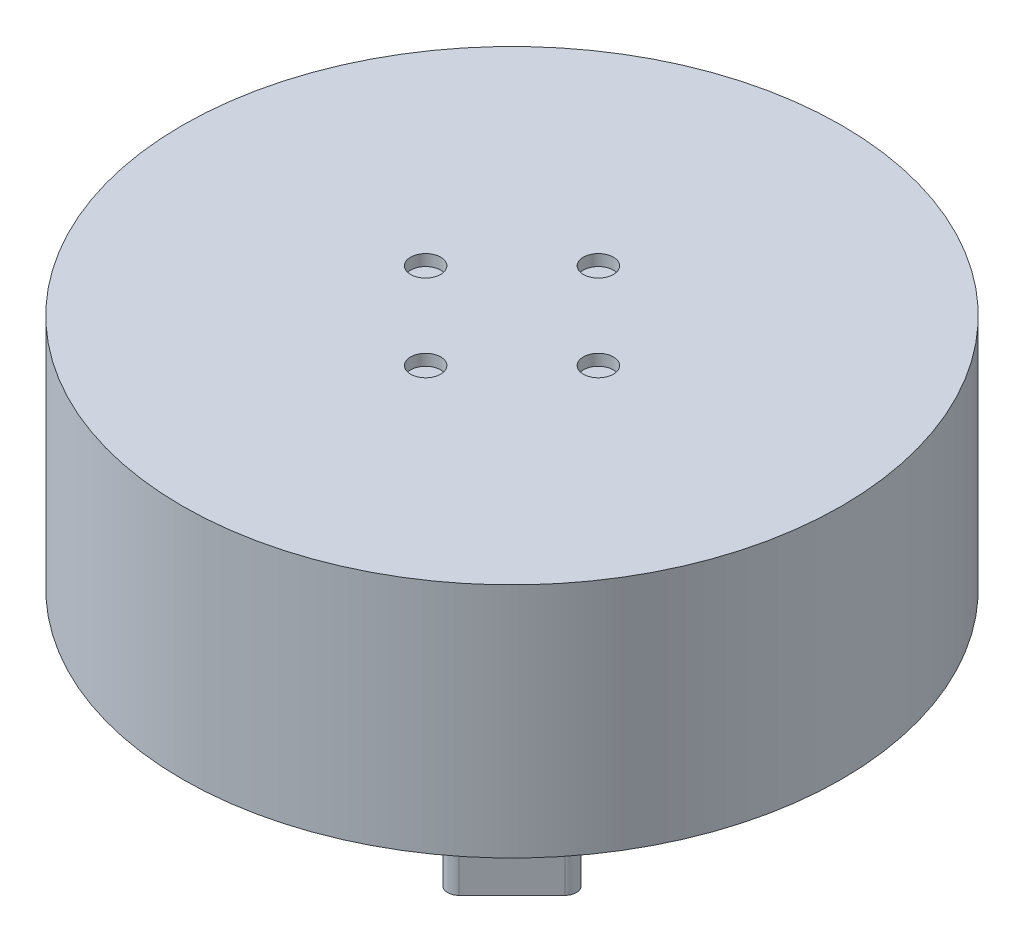
SolidWorks part; units mm, degrees
ref_plane "Front Plane" through (0, 0, 0) normal (0, 0, 1) x (1, 0, 0)
ref_plane "Top Plane" through (0, 0, 0) normal (0, 1, 0) x (1, 0, 0)
ref_plane "Right Plane" through (0, 0, 0) normal (1, 0, 0) x (0, 0, -1)
sketch "Sketch1" plane through (0, 0, 0) normal (0, 1, 0) x (1, 0, 0)
  circle A0 centre (0, 0) radius 43.9
  dimension "D1" = 87.8
extrude "Boss-Extrude1" add sketch "Sketch1" along normal blind 31.5
sketch "Sketch2" plane through (0, 0, 0) normal (0, -1, 0) x (1, 0, 0)
  circle A0 centre (0, 0) radius 18 construction
  circle A1 centre (0, 18) radius 2
  circle A2 centre (18, 0) radius 2
  circle A3 centre (0, -18) radius 2
  circle A4 centre (-18, 0) radius 2
  point P14 (0, 0)
  dimension "D1" = 36
  dimension "D2" = 4
  dimension "D3" = 4
extrude "Cut-Extrude1" cut sketch "Sketch2" against normal blind 1.5
sketch "Sketch3" plane through (0, 0, 0) normal (0, -1, 0) x (1, 0, 0)
  line L0 (0, 0) -> (0, 18) construction
  line L1 (0, 18) -> (18, 0) construction
  line L2 (18, 0) -> (0, 0) construction
  line L3 (0, 0) -> (28.2843, 28.2843) construction
  line L4 (24.7487, 31.8198) -> (31.8198, 24.7487) construction
  line L5 (26.5165, 33.5876) -> (33.5876, 26.5165) construction
  line L6 (22.981, 30.052) -> (30.052, 22.981) construction
  line L7 (25.8094, 32.8805) -> (32.8805, 25.8094)
  line L8 (23.6881, 30.7591) -> (30.7591, 23.6881)
  arc A0 (26.5165, 33.5876) -> (22.981, 30.052) centre (24.7487, 31.8198) ccw construction
  arc A1 (30.052, 22.981) -> (33.5876, 26.5165) centre (31.8198, 24.7487) ccw construction
  arc A2 (30.7591, 23.6881) -> (32.8805, 25.8094) centre (31.8198, 24.7487) ccw
  arc A3 (25.8094, 32.8805) -> (23.6881, 30.7591) centre (24.7487, 31.8198) ccw
  point P9 (28.2843, 28.2843)
  dimension "D3" = 2.5
  dimension "D1" = 40
  dimension "D2" = 10
  dimension "D4" = 1
extrude "Boss-Extrude2" add sketch "Sketch3" along normal blind 6
sketch "Sketch4" plane through (0, 31.5, 0) normal (0, 1, 0) x (1, 0, 0)
  circle A0 centre (0, 0) radius 11.5 construction
  circle A1 centre (0, 11.5) radius 2
  circle A2 centre (11.5, 0) radius 2
  circle A3 centre (0, -11.5) radius 2
  circle A4 centre (-11.5, 0) radius 2
  point P14 (0, 0)
  dimension "D2" = 4
  dimension "D3" = 4
  dimension "D1" = 23
extrude "Cut-Extrude2" cut sketch "Sketch4" against normal blind 1.5
equation "\"Np\"= 65"
equation "\"module\"= 0.5"
equation "\"pressure angle\"= 20.0deg"
equation "\"h_a\"= 0.5"
equation "\"h_b\"= 0.625"
equation "\"clr_tip_root\"= 0.125"
equation "\"dp_p\"= 32.5"
equation "\"db_p\"= 30.540010175542022"
equation "\"fw_p\"= 22.13479809822934"
equation "\"alpha_p\"= 0.8539582918412485"
equation "\"beta_p\"= 1.0613141855482722"
equation "\"Nr\"= 155"
equation "\"pressure_angle\"= 20.0deg"
equation "\"h_f\"= 0.625"
equation "\"dp_r\"= 77.5"
equation "\"db_r\"= 72.8261781109079"
equation "\"fw_r\"= 22.13479809822934"
equation "\"alpha_r\"= 0.8539582918412449"
equation "\"beta_r\"= 2.869206906263135"
equation "\"bearing_ID\"= 55"
equation "\"bearing_OD\"= 72"
equation "\"bearing_height\"= 9"
equation "\"clearance_planet\"= 1.5"
equation "\"case_dist\"= 6.5"
equation "\"Motor_case_OD_max\"= 112.3"
equation "\"case_mounting_PCD\"= 104.8"
equation "\"bearing mount thickness\"= 8"
equation "\"case_mounting_hole_dia\"= 3"
equation "\"output_mounting_PCD\"= 80"
equation "\"output_mounting_hole_dia\"= 4"
equation "\"clearance_case_mount_holes_shell_thickness\"= 1"
equation "\"motor_case_OD_base\"= 102.8"
equation "\"sec_carrier_thickness\"= 5"
equation "\"sun_coupler_hub_thickness\"= 4"
equation "\"clearance_sun_coupler_sec_carrier\"= 1.5"
equation "\"clearance_motor_and_case\"= 5"
equation "\"motor_OD\"= 87.8"
equation "\"Motor_case_thickness\"= 2.5"
equation "\"Motor_case_ID\"= 97.8"
equation "\"case_mounting_hole_shift\"= 1.0"
equation "\"output_mounting_nut_wrench_size\"= 7"
equation "\"output_mounting_nut_thickness\"= 3.2"
equation "\"case_mounting_hole_allen_socket_dia\"= 5.5"
equation "\"output_mounting_nut_depth\"= 3"
equation "\"case_mounting_bolt_depth\"= 4.5"
equation "\"Ns\"= 25"
equation "\"ring_radial_thickness\"= 5.0"
equation "\"ring_OD\"= 87.5"
equation "\"ring_to_chamfer_clearance\"= 2"
equation "\"Motor_case_OD_base_to_chamfer\"= 5"
equation "\"pattern_offset_from_motor_case_OD_base\"= 3"
equation "\"pattern_bulge_dia\"= 3"
equation "\"pattern_num_bulge\"= 18"
equation "\"pattern_depth\"= 2"
equation "\"motor_height\"= 31.5"
equation "\"case_mounting_wrench_size\"= 5.5"
equation "\"case_mounting_nut_clearance\"= 2"
equation "\"base_plate_thickness\"= 4"
equation "\"case_mounting_nut_thickness\"= 2.4"
equation "\"case_mounting_surface_height\"= 4"
equation "\"motor_mount_hole_PCD\"= 36"
equation "\"motor_mount_hole_dia\"= 4"
equation "\"motor_mount_hole_num\"= 4"
equation "\"central_hole_offset_from_motor_mount_PCD\"= 5"
equation "\"wire_slot_dist_from_center\"= 40"
equation "\"wire_slot_length\"= 10"
equation "\"wire_slot_radius\"= 2.5"
equation "\"driver_upper_holes_dist_from_center\"= 29"
equation "\"driver_lower_holes_dist_from_center\"= 13"
equation "\"driver_side_holes_dist_from_center\"= 22.5"
equation "\"driver_mount_holes_dia\"= 3"
equation "\"driver_mount_inserts_OD\"= 4.8"
equation "\"driver_mount_thickness\"= 1.5"
equation "\"driver_mount_height\"= 6"
equation "\"air_flow_hole_offset\"= 3"
equation "\"num_planet\"= 3"
equation "\"planet_pin_bolt_dia\"= 5"
equation "\"planet_pin_socket_head_dia\"= 8.5"
equation "\"carrier_PCD\"= 45.0"
equation "\"planet_shaft_dia\"= 8"
equation "\"planet_shaft_step_offset\"= 1"
equation "\"carrier_trapezoidal_support_sun_offset\"= 5"
equation "\"carrier_trapezoidal_support_hole_PCD_offset_bearing_ID\"= 4"
equation "\"carrier_trapezoidal_support_hole_dia\"= 3"
equation "\"carrier_trapezoidal_support_hole_socket_head_dia\"= 5.5"
equation "\"carrier_bearing_step_width\"= 1.5"
equation "\"standard_clearance_1_5mm\"= 1.5"
equation "\"standard_fillet_1_5mm\"= 1.5"
equation "\"sun_shaft_bearing_OD\"= 16"
equation "\"sun_shaft_bearing_width\"= 5"
equation "\"standard_bearing_insertion_chamfer\"= 0.5"
equation "\"carrier_trapezoidal_support_hole_wrench_size\"= 5.5"
equation "\"planet_pin_bolt_wrench_size\"= 8"
equation "\"planet_bearing_OD\"= 12"
equation "\"planet_bearing_width\"= 3.5"
equation "\"planet_bore\"= 10"
equation "\"D1@Boss-Extrude1\"=\"motor_height\""
equation "\"D1@Sketch1\"=\"motor_OD\""
equation "\"D1@Sketch2\"=\"motor_mount_hole_PCD\""
equation "\"D2@Sketch2\"=\"motor_mount_hole_dia\""
equation "\"D3@Sketch2\"=\"motor_mount_hole_num\""
equation "\"D1@Cut-Extrude1\"=\"standard_clearance_1_5mm\""
equation "\"D1@Sketch3\"=\"wire_slot_dist_from_center\""
equation "\"D2@Sketch3\"=\"wire_slot_length\""
equation "\"D3@Sketch3\"=\"wire_slot_radius\""
equation "\"D1@Boss-Extrude2\"=\"standard_clearance_1_5mm\"*4"
equation "\"motor_output_hole_PCD\"= 23"
equation "\"motor_output_hole_dia\"= 4"
equation "\"motor_output_hole_num\"= 4"
equation "\"D1@Sketch4\"=\"motor_output_hole_PCD\""
equation "\"D2@Sketch4\"=\"motor_output_hole_dia\""
equation "\"D3@Sketch4\"=\"motor_output_hole_num\""
equation "\"D1@Cut-Extrude2\"=\"standard_clearance_1_5mm\""
